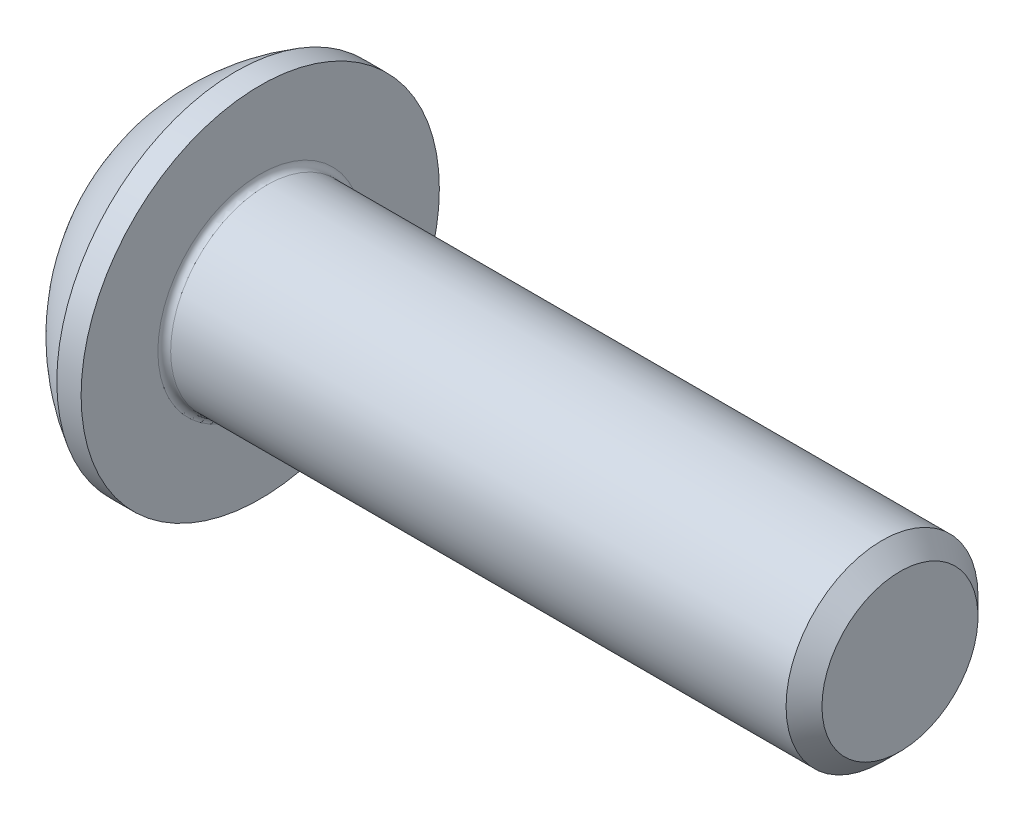
SolidWorks part; units mm, degrees
ref_plane "Plane1" through (0, 0, 0) normal (0, 0, 1) x (1, 0, 0)
ref_plane "Plane2" through (0, 0, 0) normal (0, 1, 0) x (1, 0, 0)
ref_plane "Plane3" through (0, 0, 0) normal (1, 0, 0) x (0, 0, -1)
sketch "BodySke" plane through (0, 0, 0) normal (0, 0, 1) x (1, 0, 0)
  line L0 (11.7, 0) -> (11.7, 1.2195)
  line L1 (11.4195, 1.5) -> (1.7, 1.5)
  line L2 (1.7, 1.5) -> (1.7, 2.8)
  line L3 (1.7, 2.8) -> (1.32, 2.8)
  line L4 (0, 0) -> (101.6, 0) construction
  line L5 (1.7, -2.8) -> (1.32, -2.8) construction
  line L6 (55.6768, -1.5) -> (1.7, -1.5) construction
  line L7 (11.7, 0) -> (0, 0)
  line L8 (0, 1.4) -> (0, -1.4) construction
  line L9 (0, 0) -> (0, 1.4)
  line L10 (11.7, 1.2195) -> (11.4195, 1.5)
  line L11 (11.7, -1.2195) -> (11.4195, -1.5) construction
  line L12 (2.2, 9.525) -> (2.2, -1.5) construction
  line L13 (1.7, 9.525) -> (1.7, -1.5) construction
  arc A1 (0, 1.4) -> (1.32, 2.8) centre (2.8873, 0) cw
  dimension "D1" = 2.8
  dimension "Diameter" = 3
  dimension "Length" = 10
  dimension "Head_dia" = 5.6
  dimension "Head_ht" = 1.7
  dimension "Head_side_ht" = 0.38
  dimension "Minor_dia" = 2.439
  dimension "Body_ch_ang" = 45
  dimension "Advance" = 0.5
  dimension "Thread_nom" = 10
revolve "BaseBody" add sketch "BodySke" angle 360 about L4
cosmetic thread "ThreadCosmetic" parameters "Thread_length"=9, "Thread_minor"=2.439
fillet "Fillet1" radius 0.1 1 edges at (1.7, 0, 1.5)
sketch "Sketch2" plane through (0, 0, 0) normal (0, 0, 1) x (1, 0, 0)
  line L0 (0, 1) -> (1.04, 1)
  line L1 (1.04, 1) -> (1.6174, 0)
  line L3 (1.6174, 0) -> (0, 0)
  line L4 (0, 0) -> (0, 1)
  line L5 (0, -1) -> (1.04, -1) construction
  line L6 (0, 0) -> (47.625, 0) construction
  dimension "D2" = 60
  dimension "PreBroach_depth" = 1.04
  dimension "PreBroach_dia" = 2
revolve "PreBroach" cut sketch "Sketch2" angle 360 about L6
sketch "Sketch3" plane through (0, 0, 0) normal (1, 0, 0) x (0, 0, -1)
  line L0 (-1, -0.5774) -> (-1, 0.5774)
  line L1 (-1, 0.5774) -> (0, 1.1547)
  line L2 (0, 1.1547) -> (1, 0.5774)
  line L3 (1, 0.5774) -> (1, -0.5774)
  line L4 (1, -0.5774) -> (0, -1.1547)
  line L5 (0, -1.1547) -> (-1, -0.5774)
  dimension "D1" = 1
  dimension "D2" = 1
  dimension "D3" = 2
  dimension "Hex_size" = 2
extrude "Hex" cut sketch "Sketch3" along normal blind 1.04
sketch "ThdSchSke" plane through (0, 0, 0) normal (0, 0, 1) x (1, 0, 0)
  line L0 (2.7, -1.2195) -> (2.5036, -1.5)
  line L1 (2.7, -1.2195) -> (2.8964, -1.5)
  line L2 (2.8964, -1.5) -> (2.8964, -1.875)
  line L3 (-3.175, 0) -> (5.1513, 0) construction
  line L5 (2.8964, -1.875) -> (2.5036, -1.875)
  line L6 (2.5036, -1.875) -> (2.5036, -1.5)
  dimension "Thread_minor" = 2.439
  dimension "Diameter" = 3
  dimension "Start" = 2.7
  dimension "SideAngle" = 55
  dimension "VeeAngle" = 70
  dimension "Overcut" = 3.75
revolve "ThreadSchematic" [suppressed] cut sketch "ThdSchSke" angle 360 about L3
pattern_linear "ThdSchPat" [suppressed]
equation "\"D1@BodySke\" = \"Head_dia@BodySke\" * .5"
equation "\"Thread_minor@ThreadCosmetic\" = \"Minor_dia@BodySke\""
equation "\"D1@Sketch3\" = \"Hex_size@Sketch3\" / 2"
equation "\"D2@Sketch3\" = \"D1@Sketch3\""
equation "\"D3@Sketch3\" = \"Hex_size@Sketch3\""
equation "\"Thread_length@ThreadCosmetic\" = ((sgn( (\"Length@BodySke\" - \"Advance@BodySke\" * 2.0) - \"Thread_nom@BodySke\" )-1)*( (\"Length@BodySke\" - \"Advance@BodySke\" * 2.0) - \"Thread_nom@BodySke\" ))/-2+ \"Thread_nom@BodySke\""
equation "\"Thread_minor@ThdSchSke\" = \"Minor_dia@BodySke\""
equation "\"Diameter@ThdSchSke\" = \"Diameter@BodySke\""
equation "\"Overcut@ThdSchSke\" = \"Diameter@BodySke\" * 1.25"
equation "\"Start@ThdSchSke\" = \"Head_ht@BodySke\" + \"Length@BodySke\" - \"Thread_length@ThreadCosmetic\"  '---Non-countersunk---"
equation "\"Num_threads@ThdSchPat\" = int( \"Thread_length@ThreadCosmetic\" / \"Advance@BodySke\" + 0.999 )  + 1"
equation "\"Advance@ThdSchPat\" = \"Thread_length@ThreadCosmetic\" /  (\"Num_threads@ThdSchPat\" - 1) 'relax it"
equation "\"Num_threads@ThdSchPat\" = \"Num_threads@ThdSchPat\" - sgn( \"Num_threads@ThdSchPat\" - 1) '---chamfered tips only---"
